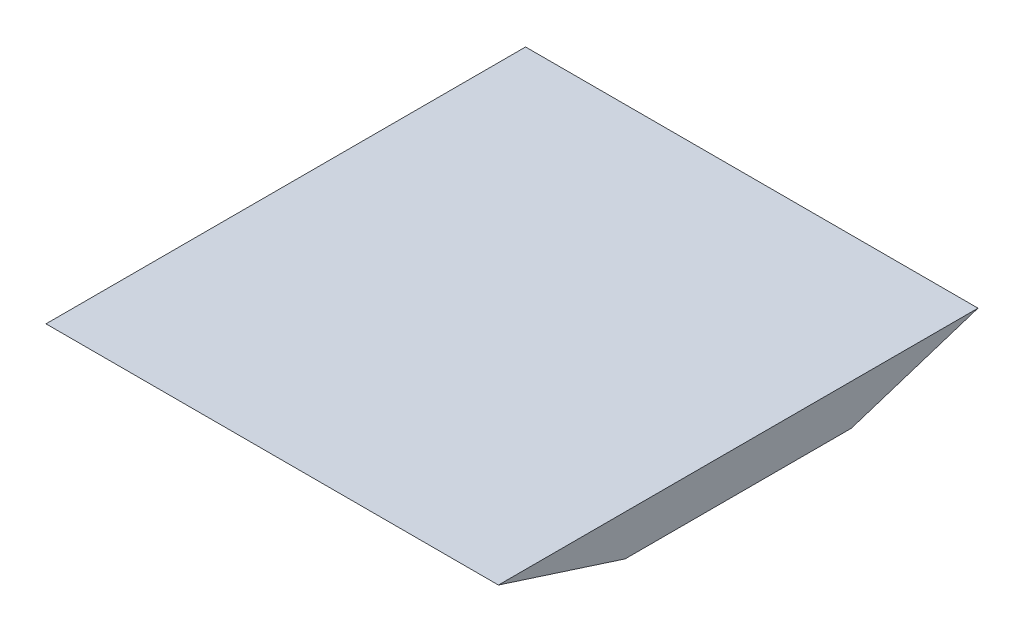
SolidWorks part; units mm, degrees
ref_plane "Front Plane" through (0, 0, 0) normal (0, 0, 1) x (1, 0, 0)
ref_plane "Top Plane" through (0, 0, 0) normal (0, 1, 0) x (1, 0, 0)
ref_plane "Right Plane" through (0, 0, 0) normal (1, 0, 0) x (0, 0, -1)
sketch "Sketch1" plane through (0, 0, 0) normal (1, 0, 0) x (0, 0, -1)
  line L0 (0, 0) -> (106, 0)
  line L1 (106, 0) -> (78, -9)
  line L2 (78, -9) -> (28, -9)
  line L3 (28, -9) -> (0, 0)
  point P3 (53, 0)
  dimension "D1" = 50
  dimension "D2" = 28
  dimension "D3" = 28
  dimension "D4" = 9
extrude "Boss-Extrude1" add sketch "Sketch1" along normal blind 100
